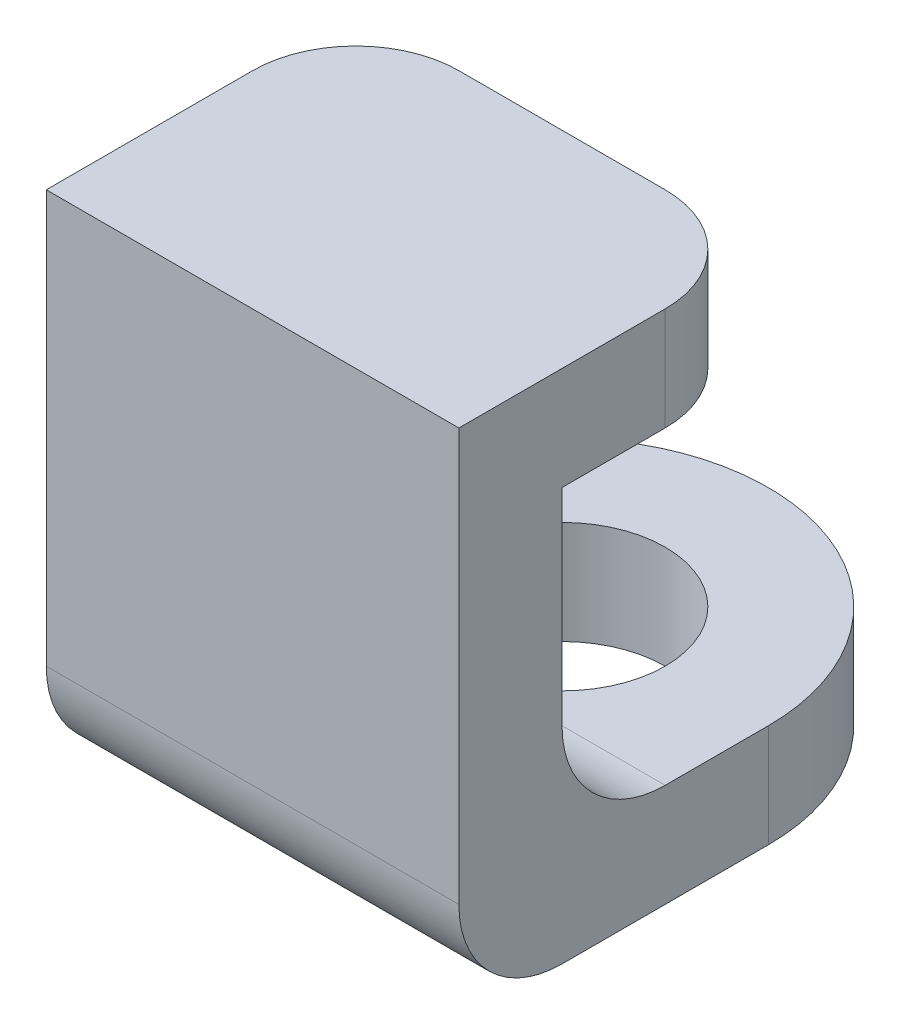
SolidWorks part; units mm, degrees
ref_plane "前基準面" through (0, 0, 0) normal (0, 0, 1) x (1, 0, 0)
ref_plane "上基準面" through (0, 0, 0) normal (0, 1, 0) x (1, 0, 0)
ref_plane "右基準面" through (0, 0, 0) normal (1, 0, 0) x (0, 0, -1)
sketch "草圖1" plane through (0, 0, 0) normal (1, 0, 0) x (0, 0, -1)
  line L0 (0, 0) -> (-3, 0)
  line L1 (-3, 0) -> (-3, -4)
  line L2 (-2, -5) -> (2, -5)
  line L3 (2, -5) -> (2, -4)
  line L4 (2, -4) -> (-1, -4)
  line L5 (-2, -3) -> (-2, -1)
  line L6 (-2, -1) -> (0, -1)
  line L7 (0, -1) -> (0, 0)
  arc A0 (-1, -4) -> (-2, -3) centre (-1, -3) cw
  arc A1 (-3, -4) -> (-2, -5) centre (-2, -4) ccw
  point P13 (-3, -5)
  dimension "D7" = 1
  dimension "D1" = 3
  dimension "D2" = 2
  dimension "D3" = 5
  dimension "D4" = 5
  dimension "D5" = 1
  dimension "D6" = 1
extrude "填料-伸長1" add sketch "草圖1" along normal blind 4
sketch "草圖2" plane through (0, 0, 0) normal (0, 1, 0) x (1, 0, 0)
  line L0 (1, 0) -> (3, 0)
  line L1 (4, -1) -> (4, -1.2188)
  line L2 (4, 0) -> (4, -3) construction
  line L4 (0, 0) -> (0, -3) construction
  line L5 (0, -1.2188) -> (0, -1)
  line L6 (1, 0) -> (0, 0)
  line L7 (0, 0) -> (0, -1.2188)
  line L8 (3, 0) -> (4, 0)
  line L9 (4, 0) -> (4, -1)
  arc A0 (3, 0) -> (4, -1) centre (3, -1) cw
  arc A1 (1, 0) -> (0, -1) centre (1, -1) ccw
  point P12 (4, 0)
  point P15 (0, 0)
  line M7 (0, 0) -> (0, -3)
  line M9 (4, -3) -> (4, 0)
  line M10 (4, 0) -> (0, 0)
  dimension "D1" = 1
extrude "除料-伸長1" cut sketch "草圖2" against normal blind 3 contours A1 M10 M7 | A0 M10 M9
sketch "草圖3" plane through (0, -5, 0) normal (0, -1, 0) x (1, 0, 0)
  line L0 (0, -2) -> (0, -0.3618)
  line L1 (0, 2) -> (0, -2) construction
  line L3 (4, 2) -> (4, -2) construction
  line L4 (4, -0.3618) -> (4, -2)
  line L5 (2, -2) -> (0, -2)
  line L6 (0, -0.3618) -> (0, 2)
  line L7 (0, 2) -> (4, 2)
  line L8 (4, 2) -> (4, 0)
  line L9 (2, -2) -> (2, 0.3636) construction
  arc A0 (0, 0) -> (4, 0) centre (2, 0) ccw
  line M9 (0, 2) -> (0, -2)
  line M10 (0, -2) -> (4, -2)
  line M11 (4, -2) -> (4, 2)
  dimension "D1" = 2
extrude "除料-伸長2" cut sketch "草圖3" against normal blind 3 and the other way through all contours A0 L6 M9 M10 | A0 M10 M11
sketch "草圖4" plane through (0, -5, 0) normal (0, -1, 0) x (1, 0, 0)
  circle A0 centre (2, 0) radius 1
  dimension "D1" = 2
extrude "除料-伸長3" cut sketch "草圖4" against normal blind 3
